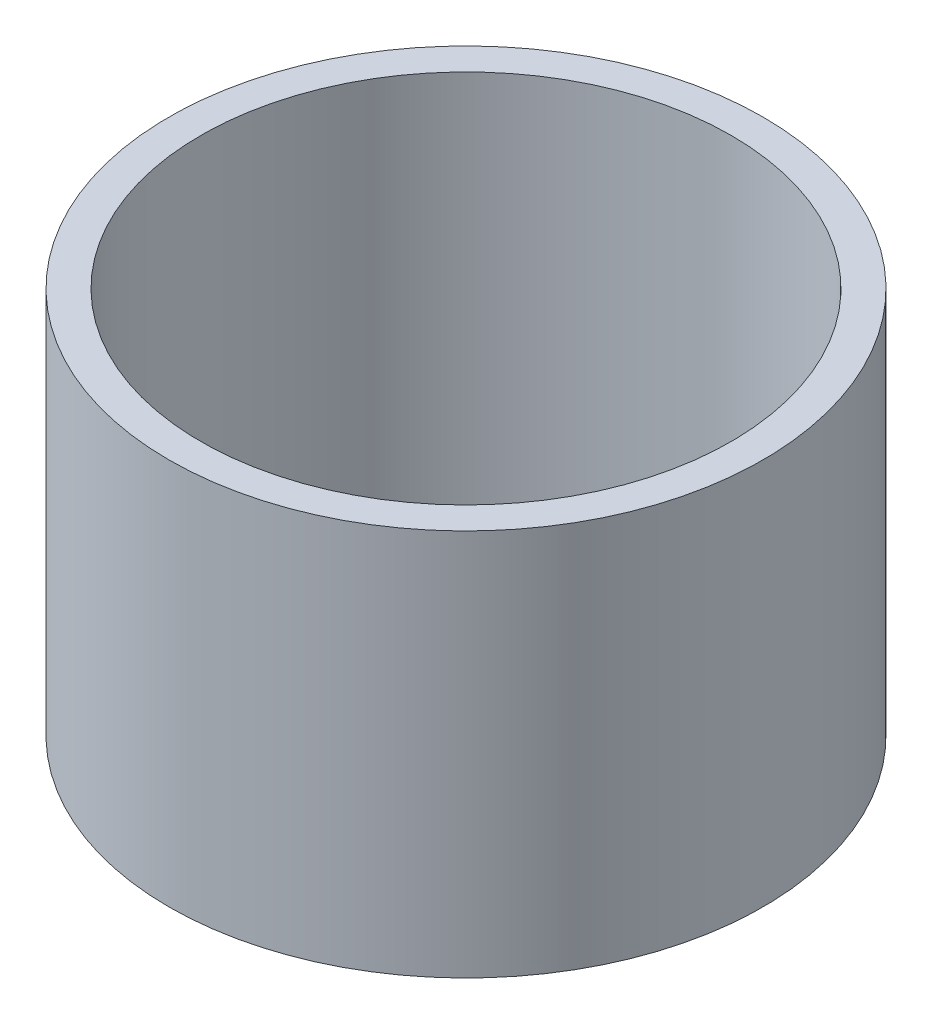
SolidWorks part; units mm, degrees
ref_plane "Front Plane" through (0, 0, 0) normal (0, 0, 1) x (1, 0, 0)
ref_plane "Top Plane" through (0, 0, 0) normal (0, 1, 0) x (1, 0, 0)
ref_plane "Right Plane" through (0, 0, 0) normal (1, 0, 0) x (0, 0, -1)
sketch "Sketch1" plane through (0, 0, 0) normal (0, 0, 1) x (1, 0, 0)
  line L0 (0, -8.9526) -> (0, 0) construction
  line L1 (-12.5, 0) -> (-12.5, -18.25)
  line L2 (-12.5, -18.25) -> (-14, -18.25)
  line L3 (-14, -18.25) -> (-14, 0)
  line L4 (-14, 0) -> (-12.5, 0)
  dimension "D1" = 28
  dimension "D2" = 1.5
  dimension "D3" = 18.25
revolve "Revolve1" add sketch "Sketch1" angle 360 about L0
